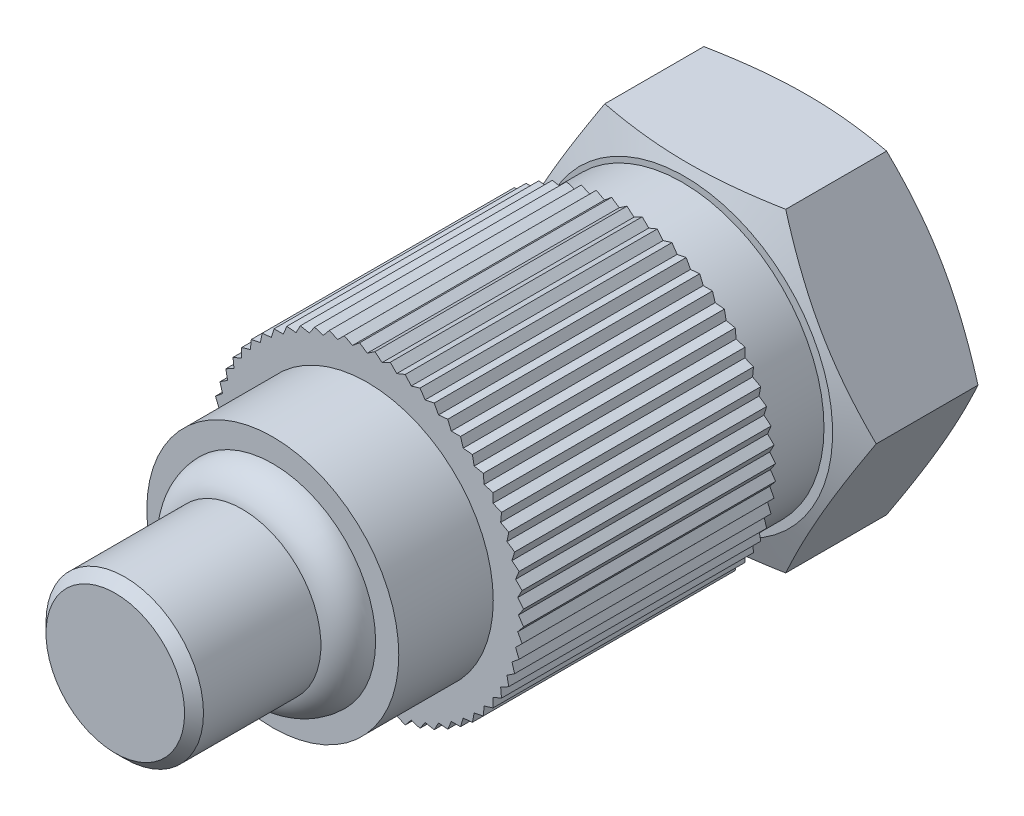
SolidWorks part; units mm, degrees
material "AISI 316  (SS)"
ref_plane "Front Plane" through (0, 0, 0) normal (0, 0, 1) x (1, 0, 0)
ref_plane "Top Plane" through (0, 0, 0) normal (0, 1, 0) x (1, 0, 0)
ref_plane "Right Plane" through (0, 0, 0) normal (1, 0, 0) x (0, 0, -1)
sketch "Sketch1" plane through (0, 0, 0) normal (0, 0, 1) x (1, 0, 0)
  line L1 (-5.7735, 0) -> (-2.8868, -5)
  line L2 (-2.8868, -5) -> (2.8868, -5)
  line L3 (2.8868, -5) -> (5.7735, 0)
  line L4 (5.7735, 0) -> (2.8868, 5)
  line L5 (2.8868, 5) -> (-2.8868, 5)
  line L6 (-2.8868, 5) -> (-5.7735, 0)
  circle A0 centre (0, 0) radius 5 construction
  dimension "D1" = 10
extrude "Boss-Extrude1" add sketch "Sketch1" along normal blind 4
sketch "Sketch2" plane through (0, 0, 4) normal (0, 0, 1) x (1, 0, 0)
  circle A0 centre (0, 0) radius 4.5
  dimension "D1" = 9
extrude "Boss-Extrude2" add sketch "Sketch2" along normal blind 2
sketch "Sketch3" plane through (0, 0, 6) normal (0, 0, 1) x (1, 0, 0)
  circle A0 centre (0, 0) radius 5
  dimension "D1" = 10
extrude "Boss-Extrude3" add sketch "Sketch3" along normal blind 8
sketch "Sketch4" plane through (0, 0, 14) normal (0, 0, 1) x (1, 0, 0)
  circle A0 centre (0, 0) radius 4
  dimension "D1" = 8
extrude "Boss-Extrude4" add sketch "Sketch4" along normal blind 3
sketch "Sketch5" plane through (0, 0, 0) normal (1, 0, 0) x (0, 0, -1)
  line L0 (-17, 4) -> (-17, -4) construction
  line L1 (-17, 0) -> (-27.7933, 0) construction
  circle A0 centre (-17, 2.2646) radius 1
  dimension "D1" = 2
revolve "Revolve1" add sketch "Sketch5" angle 360 about L1
sketch "Sketch6" plane through (0, 0, 17) normal (0, 0, 1) x (1, 0, 0)
  circle A0 centre (0, 0) radius 2.5
  dimension "D1" = 5
extrude "Boss-Extrude5" add sketch "Sketch6" along normal blind 5
sketch "Sketch7" plane through (0, 0, 0) normal (0, 0, -1) x (-1, 0, 0)
  circle A0 centre (0, 0) radius 0.075
  dimension "D1" = 0.15
extrude "Cut-Extrude1" cut sketch "Sketch7" against normal blind 5
sketch "Sketch8" plane through (0, 0, 0) normal (0, 1, 0) x (1, 0, 0)
  line L0 (4.7735, 0) -> (6.075, -0.5)
  line L1 (6.075, -0.5) -> (6.075, 0)
  line L2 (6.075, 0) -> (4.7735, 0)
  line L3 (0.075, 0) -> (0.075, -2.2257) construction
  line L4 (5.7735, 0) -> (2.8868, 0) construction
  line L5 (5.7735, -4) -> (5.7735, 0) construction
  dimension "D1" = 6
  dimension "D2" = 0.5
  dimension "D3" = 1
revolve "Cut-Revolve1" cut sketch "Sketch8" angle 360 about L3
chamfer "Chamfer1" distance 0.3 angle 45 1 edges at (2.5, 0, 22)
ref_plane "Plane1" through (0, 0, 2) normal (0, 0, -1) x (-1, 0, 0)
mirror "Mirror1" about plane through (0, 0, 2) normal (0, 0, -1) of "Cut-Revolve1"
sketch "Sketch10" plane through (0, 0, 22) normal (0, 0, 1) x (1, 0, 0)
sketch "Sketch11" plane through (0, 0, 14) normal (0, 0, 1) x (1, 0, 0)
  line L0 (0, 5) -> (0, 4.8)
  line L1 (2.8868, 5) -> (-2.8868, 5) construction
  line L2 (0, 4.8) -> (0.3, 5)
  line L3 (0.3, 5) -> (0, 5)
  dimension "D1" = 0.3
  dimension "D2" = 0.2
extrude "Cut-Extrude4" cut sketch "Sketch11" against normal up to surface (8 mm away) up to face at (4.5, 0, 6)
mirror "Mirror2" about plane through (0, 0, 0) normal (1, 0, 0) of "Cut-Extrude4"
pattern_circular "CirPattern1" count 64 over 360 about axis through (0, 0, 0) along (0, 0, 1) of "Mirror2", "Cut-Extrude4"
sketch "Sketch12" plane through (0, 0, 0) normal (0, 0, 1) x (1, 0, 0)
  circle A0 centre (0, 0) radius 2.5 construction
  text T0 "CENTIGRADE" font "Cambria" height in points 5
  dimension "D1" = 5
extrude "Cut-Extrude6" cut sketch "Sketch12" along normal blind 0.1
